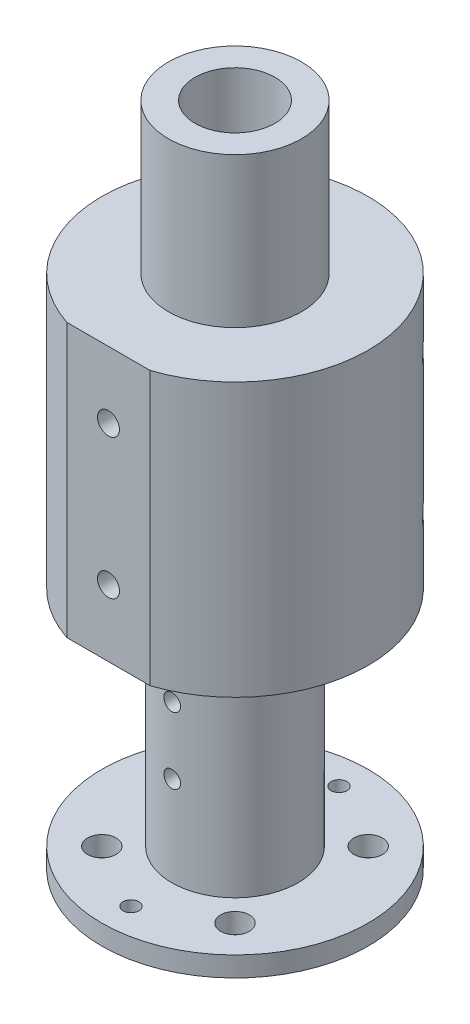
SolidWorks part; units mm, degrees
material "3.3547 (EN-AW 5083)"
ref_plane "Front Plane" through (0, 0, 0) normal (0, 0, 1) x (1, 0, 0)
ref_plane "Top Plane" through (0, 0, 0) normal (0, 1, 0) x (1, 0, 0)
ref_plane "Right Plane" through (0, 0, 0) normal (1, 0, 0) x (0, 0, -1)
sketch3d "3DSketch1"
  line L0 (9.7843, 77.5, -18.5) -> (18.5, 77.5, -9.7843) construction
  line L1 (9.7843, 36.5, -18.5) -> (18.5, 36.5, -9.7843) construction
  line L2 (9.7843, 77.5, -18.5) -> (18.5, 77.5, -9.7843)
  line L3 (9.7843, 36.5, -18.5) -> (18.5, 36.5, -9.7843)
  circle A0 centre (0, 75.0994, 0) radius 1.75 construction
  circle A1 centre (0, 100, 0) radius 20
  circle A2 centre (0, 100, 0) radius 20
  circle A3 centre (0, 70.0994, 0) radius 3.3252 construction
  circle A4 centre (0, 66.9, 0) radius 5.5 construction
  circle A5 centre (0, 10.1, 0) radius 5.5 construction
  circle A6 centre (0, 10, 0) radius 5.0866 construction
  circle A7 centre (0, 0, 0) radius 20 construction
  circle A8 centre (0, 75.0994, 0) radius 1.75
  circle A9 centre (0, 70.0994, 0) radius 3.3252
  circle A10 centre (0, 66.9, 0) radius 5.5
  circle A11 centre (0, 10.1, 0) radius 5.5
  circle A12 centre (0, 10, 0) radius 5.0866
  circle A13 centre (0, 0, 0) radius 20
  circle A15 centre (-14.1421, 67.5, -14.1421) radius 2.15
  circle A16 centre (-14.1421, 67.5, -14.1421) radius 2.15
  circle A17 centre (-14.1421, 46.5, -14.1421) radius 2.15
  circle A18 centre (-14.1421, 46.5, -14.1421) radius 2.15
  circle A19 centre (14.1421, 46.5, -14.1421) radius 2.15
  circle A20 centre (14.1421, 46.5, -14.1421) radius 2.15
  circle A21 centre (14.1421, 67.5, -14.1421) radius 2.15
  circle A22 centre (14.1421, 67.5, -14.1421) radius 2.15
  point P2 (0, 76.8494, 0)
  point P5 (0, 120, 0)
  point P7 (0, 120, 0)
  point P10 (0, 73.4247, 0)
  point P13 (0, 61.4, 0)
  point P16 (0, 15.6, 0)
  point P19 (0, 15.0866, 0)
  point P22 (0, 20, 0)
  point P24 (0, 76.8494, 0)
  point P26 (0, 73.4247, 0)
  point P28 (0, 61.4, 0)
  point P30 (0, 15.6, 0)
  point P32 (0, 15.0866, 0)
  point P34 (0, 20, 0)
  point P40 (-12.6219, 67.5, -12.6219)
  point P42 (-12.6219, 67.5, -12.6219)
  point P45 (-12.6219, 46.5, -12.6219)
  point P47 (-12.6219, 46.5, -12.6219)
  point P50 (12.6219, 46.5, -12.6219)
  point P52 (12.6219, 46.5, -12.6219)
  point P55 (12.6219, 67.5, -12.6219)
  point P57 (12.6219, 67.5, -12.6219)
  dimension "D1" = 0
  dimension "D2" = 0
  dimension "D3" = 0
  dimension "D4" = 0
  dimension "D5" = 0
sketch "Sketch1" plane through (0, 0, 0) normal (0, 0, 1) x (1, 0, 0)
  line L0 (0, 0) -> (0, 103.5557) construction
  line L1 (20, 0) -> (-20, 0) construction
  line L2 (20, 100) -> (-20, 100) construction
  line L3 (20, 0) -> (-20, 0) construction
  line L4 (20, 100) -> (-20, 100) construction
  line L5 (5.5, 66.9) -> (-5.5, 66.9) construction
  line L6 (5.5, 66.9) -> (-5.5, 66.9) construction
  line L8 (5.5, 66.9) -> (5.5, 0)
  line L9 (5.5, 0) -> (20, 0)
  line L10 (20, 0) -> (20, 3)
  line L11 (20, 3) -> (9.5, 3)
  line L12 (9.5, 3) -> (9.5, 36.5)
  line L13 (9.5, 36.5) -> (20, 36.5)
  line L14 (20, 36.5) -> (20, 77.5)
  line L15 (20, 77.5) -> (10, 77.5)
  line L16 (10, 77.5) -> (10, 100)
  line L17 (10, 100) -> (6, 100)
  line L18 (9.7843, 77.5) -> (18.5, 77.5) construction
  line L19 (9.7843, 36.5) -> (18.5, 36.5) construction
  line L20 (6, 100) -> (6, 66.9)
  line L21 (6, 66.9) -> (5.5, 66.9)
  dimension "D1" = 3
  dimension "D2" = 4
  dimension "D3" = 20
  dimension "D4" = 0.5
revolve "Revolve1" add sketch "Sketch1" angle 360 about L0
cosmetic thread "Cosmetic Thread1" parameters "D1"=20, "D2"=17.252
sketch "Sketch6" plane through (0, 77.5, 0) normal (0, 1, 0) x (1, 0, 0)
  line L0 (-6.245, -19) -> (6.245, -19)
  circle A0 centre (0, 0) radius 20 construction
  arc A1 (-6.245, -19) -> (6.245, -19) centre (0, 0) ccw
  dimension "D1" = 19
extrude "Cut-Extrude2" cut sketch "Sketch6" against normal up to next
hole_wizard "M4 Tapped Hole1" positions "3DSketch2" profile "Sketch2" tap size "M4" standard "DIN"
sketch3d "3DSketch2"
  line L0 (0, 77.5, 19) -> (0, 36.5, 19) construction
  line L1 (-14.1421, 67.5, -14.1421) -> (0, 67.5, 19) construction
  line L2 (-14.1421, 46.5, -14.1421) -> (0, 46.5, 19) construction
  line L3 (6.245, 77.5, 19) -> (-6.245, 77.5, 19) construction
  line L4 (6.245, 36.5, 19) -> (-6.245, 36.5, 19) construction
  point P17 (14.1421, 67.5, -14.1421)
  point P19 (14.1421, 46.5, -14.1421)
  point P21 (-14.1421, 46.5, -14.1421)
  point P23 (-14.1421, 67.5, -14.1421)
  point P78 (0, 67.5, 19)
  point P80 (0, 46.5, 19)
  dimension "D1" = 36.0333
sketch "Sketch2" plane through (14.1421, 67.5, -14.1421) normal (0, 1, 0) x (-0.7071, 0, -0.7071)
  line L0 (0, 0) -> (0, 11.0914)
  line L1 (0, 11.0914) -> (1.65, 10.1)
  line L2 (1.65, 10.1) -> (1.65, 0)
  line L5 (1.65, 0) -> (0, 0)
  line L10 (0, 11.0914) -> (-1.65, 10.1) construction
  line L11 (0, -6.35) -> (0, 107.95) construction
  dimension "Tap Drill Dia." = 3.3
  dimension "Tap Drill Depth" = 10.1
  dimension "Drill Angle" = 118
cosmetic thread "Hole Thread15" parameters "D1"=8, "D2"=4
cosmetic thread "Hole Thread16" parameters "D1"=8, "D2"=4
sketch "Sketch3" plane through (0, 0, 0) normal (0, -1, 0) x (1, 0, 0)
  line L0 (0, 0) -> (0, 20) construction
  line L1 (0, 0) -> (0, -20) construction
  circle A0 centre (0, 0) radius 20 construction
  arc A1 (4.8188, -2.6513) -> (-4.8188, -2.6513) centre (0, -0.6784) cw
  arc A2 (-4.8188, -2.6513) -> (4.8188, -2.6513) centre (0, 0.0759) cw
  arc A3 (0, 5.5) -> (0, -5.5) centre (0, 0) ccw construction
  dimension "D1" = 5.207
  dimension "D2" = 5.537
  dimension "D4" = 5.5
  dimension "D5" = 0.6784
  dimension "D3" = 0.7543
extrude "Cut-Extrude1" cut sketch "Sketch3" against normal up to next
hole_wizard "M3 Tapped Hole1" positions "3DSketch3" profile "Sketch4" tap size "M3" standard "DIN"
sketch3d "3DSketch3"
  line L0 (0, 36.5, 9.5) -> (0, 3, 9.5) construction
  circle A0 centre (0, 36.5, 0) radius 9.5 construction
  circle A1 centre (0, 3, 0) radius 9.5 construction
  point P5 (0, 27, 0)
  point P8 (0, -6.5, 0)
  point P9 (0, 26.5, 9.5)
  point P11 (0, 16.5, 9.5)
  dimension "D2" = 10
  dimension "D1" = 10
sketch "Sketch4" plane through (0, 16.5, 9.5) normal (1, 0, 0) x (0, -1, 0)
  line L0 (0, 0) -> (0, 3.8871)
  line L1 (0, 3.8871) -> (1.25, 3.8871)
  line L2 (1.25, 3.8871) -> (1.25, 0)
  line L5 (1.25, 0) -> (0, 0)
  line L11 (0, -6.35) -> (0, 107.95) construction
  dimension "Thru Tap Drill Dia." = 2.5
  dimension "Thru Tap Drill Depth" = 3.8871
cosmetic thread "Hole Thread7" parameters "D2"=3
cosmetic thread "Hole Thread8" parameters "D2"=3
sketch "Sketch9" plane through (0, 0, 0) normal (0, -1, 0) x (-1, 0, 0)
  line L0 (0, 15.621) -> (0, -15.621) construction
  point P0 (0, -15.621)
  point P3 (0, 15.621)
  point P14 (0, 0)
  dimension "D1" = 31.242
hole_wizard "Ø2.4mm Dowel Hole1" positions "Sketch9" profile "Sketch8" hole size "3/32" standard "ANSI Inch"
sketch "Sketch8" plane through (0, 0, 15.621) normal (1, 0, 0) x (0, 0, -1)
  line L0 (0, 0) -> (0, 3)
  line L1 (0, 3) -> (1.1906, 3)
  line L2 (1.1906, 3) -> (1.1906, 0)
  line L5 (1.1906, 0) -> (0, 0)
  line L11 (0, -6.35) -> (0, 107.95) construction
  dimension "Thru Hole Dia." = 2.3812
  dimension "Thru Hole Depth" = 3
sketch "Sketch12" plane through (0, 3, 0) normal (0, 1, 0) x (1, 0, 0)
  line L1 (-15, -15) -> (15, -15) construction
  line L2 (-15, -15) -> (-15, 15) construction
  line L3 (-15, 15) -> (15, 15) construction
  line L4 (15, -15) -> (15, 15) construction
  line L5 (-15, -15) -> (15, 15) construction
  line L6 (-15, 15) -> (15, -15) construction
  point P1 (0, 0)
  point P88 (-15, 15)
  point P90 (15, 15)
  point P92 (15, -15)
  point P94 (-15, -15)
  dimension "D1" = 30
hole_wizard "M4 Clearance Hole1" positions "Sketch12" profile "Sketch11" hole size "M4" standard "DIN"
sketch "Sketch11" plane through (0, 3, 0) normal (1, 0, 0) x (0, 0, 1)
  line L0 (0, 0) -> (0, 3)
  line L1 (0, 3) -> (2.15, 3)
  line L2 (2.15, 3) -> (2.15, 0)
  line L5 (2.15, 0) -> (0, 0)
  line L11 (0, -6.35) -> (0, 107.95) construction
  dimension "Thru Hole Dia." = 4.3
  dimension "Thru Hole Depth" = 3
sketch "Sketch15" plane through (0, 3, 0) normal (0, 1, 0) x (1, 0, 0)
  line L1 (-10, -10) -> (10, -10) construction
  line L2 (-10, -10) -> (-10, 10) construction
  line L3 (-10, 10) -> (10, 10) construction
  line L4 (10, -10) -> (10, 10) construction
  line L5 (-10, -10) -> (10, 10) construction
  line L6 (-10, 10) -> (10, -10) construction
  point P1 (0, 0)
  point P118 (-10, 10)
  point P120 (10, 10)
  point P122 (10, -10)
  point P124 (-10, -10)
  dimension "D1" = 20
hole_wizard "M4 Clearance Hole2" positions "Sketch15" profile "Sketch14" hole size "M4" standard "DIN" end condition up to next
sketch "Sketch14" plane through (-10, 3, 10) normal (1, 0, 0) x (0, 0, 1)
  line L0 (0, 0) -> (0, 3)
  line L1 (0, 3) -> (2.15, 3)
  line L2 (2.15, 3) -> (2.15, 0)
  line L5 (2.15, 0) -> (0, 0)
  line L11 (0, -6.35) -> (0, 107.95) construction
  dimension "Thru Hole Dia." = 4.3
  dimension "Thru Hole Depth" = 3
